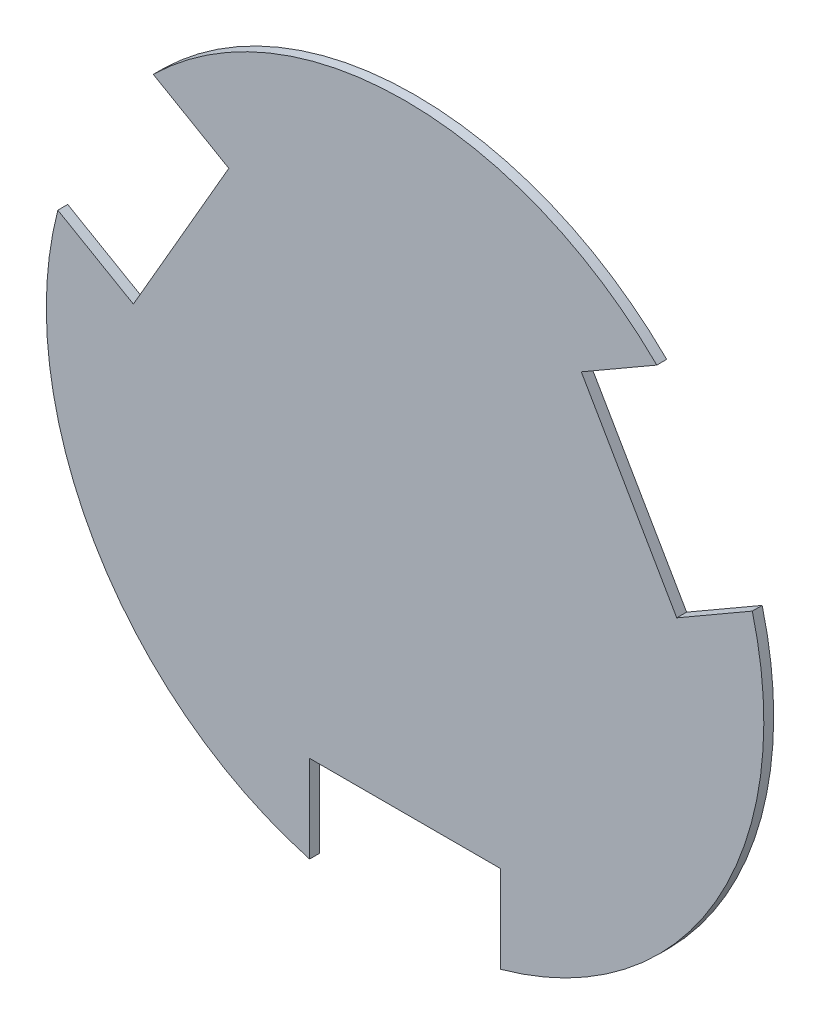
SolidWorks part; units mm, degrees
ref_plane "Plan de face" through (0, 0, 0) normal (0, 0, 1) x (1, 0, 0)
ref_plane "Plan de dessus" through (0, 0, 0) normal (0, 1, 0) x (1, 0, 0)
ref_plane "Plan de droite" through (0, 0, 0) normal (1, 0, 0) x (0, 0, -1)
sketch "Esquisse2" plane through (0, 0, 0) normal (0, 0, 1) x (1, 0, 0)
  circle A0 centre (0, 0) radius 109
  dimension "D1" = 218
extrude "Boss.-Extru.1" add sketch "Esquisse2" along normal blind 3
sketch "Esquisse3" plane through (0, 0, 3) normal (0, 0, 1) x (1, 0, 0)
  line L0 (0, 148.1699) -> (0, -178.9257) construction
  line L1 (-29, -120.9891) -> (29, -120.9891)
  line L2 (-29, -120.9891) -> (-29, -78.5714)
  line L3 (-29, -78.5714) -> (29, -78.5714)
  line L4 (29, -120.9891) -> (29, -78.5714)
  line L5 (-90.2796, 85.6093) -> (-119.2796, 35.3798)
  line L6 (-90.2796, 85.6093) -> (-53.5448, 64.4004)
  line L7 (-53.5448, 64.4004) -> (-82.5448, 14.171)
  line L8 (-119.2796, 35.3798) -> (-82.5448, 14.171)
  line L9 (119.2796, 35.3798) -> (90.2796, 85.6093)
  line L10 (119.2796, 35.3798) -> (82.5448, 14.171)
  line L11 (82.5448, 14.171) -> (53.5448, 64.4004)
  line L12 (90.2796, 85.6093) -> (53.5448, 64.4004)
  point P18 (0, 0)
  dimension "D1" = 3
  dimension "D2" = 58
  dimension "D3" = 78.5714
extrude "Enlèv. mat.-Extru.1" cut sketch "Esquisse3" against normal blind 3
